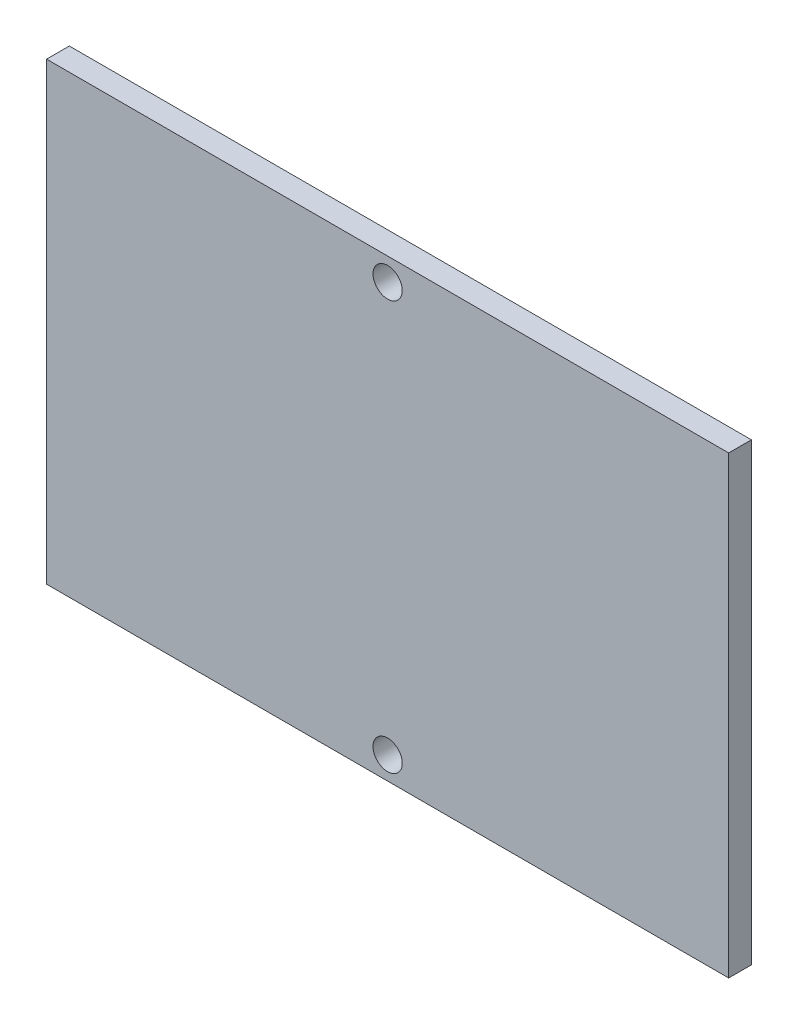
SolidWorks part; units mm, degrees
material "ABS PC"
ref_plane "Front Plane" through (0, 0, 0) normal (0, 0, 1) x (1, 0, 0)
ref_plane "Top Plane" through (0, 0, 0) normal (0, 1, 0) x (1, 0, 0)
ref_plane "Right Plane" through (0, 0, 0) normal (1, 0, 0) x (0, 0, -1)
sketch "Sketch2" plane through (0, 0, 0) normal (0, 0, 1) x (1, 0, 0)
  line L1 (-61.0577, 42.1909) -> (15.1423, 42.1909)
  line L2 (-61.0577, 42.1909) -> (-61.0577, -8.6091)
  line L3 (-61.0577, -8.6091) -> (15.1423, -8.6091)
  line L4 (15.1423, 42.1909) -> (15.1423, -8.6091)
  line L5 (-61.0577, 42.1909) -> (15.1423, -8.6091) construction
  line L6 (-61.0577, -8.6091) -> (15.1423, 42.1909) construction
  point P0 (-22.9577, 16.7909)
  dimension "D1" = 76.2
  dimension "D2" = 50.8
extrude "Boss-Extrude1" add sketch "Sketch2" along normal blind 2.54 contours L3 L4 L1 L2
sketch "Sketch3" plane through (0, 0, 2.54) normal (0, 0, 1) x (1, 0, 0)
  line L0 (15.1423, 42.1909) -> (15.1423, -8.6091) construction
  line L1 (-61.0577, 42.1909) -> (15.1423, 42.1909) construction
  circle A0 centre (-22.9577, 39.6509) radius 1.631
  dimension "D2" = 2.54
  dimension "D1" = 38.1
sketch "Sketch6" plane through (0, 0, 2.54) normal (0, 0, 1) x (1, 0, 0)
  circle A0 centre (-22.9577, 39.6509) radius 1.631
extrude "Cut-Extrude1" cut sketch "Sketch6" against normal through all
sketch "Sketch7" plane through (0, 0, 2.54) normal (0, 0, 1) x (1, 0, 0)
  line L0 (15.1423, 42.1909) -> (15.1423, -8.6091) construction
  line L1 (-61.0577, -8.6091) -> (15.1423, -8.6091) construction
  circle A0 centre (-22.9577, -6.0691) radius 1.631
  dimension "D1" = 38.1
  dimension "D2" = 2.54
extrude "Cut-Extrude2" cut sketch "Sketch7" against normal through all
